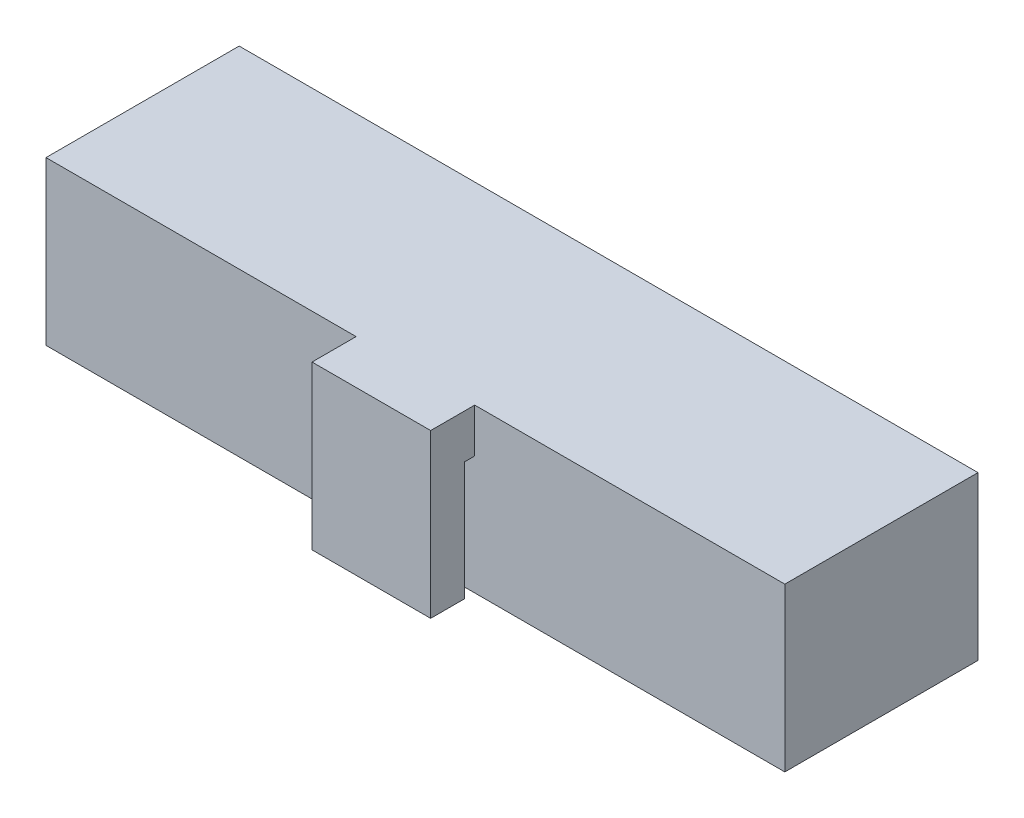
SolidWorks part; units mm, degrees
ref_plane "Plan de face" through (0, 0, 0) normal (0, 0, 1) x (1, 0, 0)
ref_plane "Plan de dessus" through (0, 0, 0) normal (0, 1, 0) x (1, 0, 0)
ref_plane "Plan de droite" through (0, 0, 0) normal (1, 0, 0) x (0, 0, -1)
sketch "Esquisse1" plane through (0, 0, 0) normal (0, 0, 1) x (1, 0, 0)
  line L1 (-10.9, -2.4) -> (10.9, -2.4)
  line L2 (-10.9, -2.4) -> (-10.9, 2.4)
  line L3 (-10.9, 2.4) -> (10.9, 2.4)
  line L4 (10.9, -2.4) -> (10.9, 2.4)
  line L5 (-10.9, -2.4) -> (10.9, 2.4) construction
  line L6 (-10.9, 2.4) -> (10.9, -2.4) construction
  point P0 (0, 0)
  dimension "D1" = 21.8
  dimension "D2" = 4.8
extrude "Boss.-Extru.1" add sketch "Esquisse1" along normal blind 7
sketch "Esquisse2" plane through (0, 0, 7) normal (0, 0, 1) x (1, 0, 0)
  line L0 (-1.75, -6.7758) -> (-1.75, 6.0976)
  line L1 (1.75, -7.2459) -> (1.75, 4.6423)
  line L2 (10.9, 2.4) -> (-10.9, 2.4) construction
  line L3 (-10.9, -2.4) -> (-1.75, -2.4)
  line L4 (-10.9, -2.4) -> (-10.9, 2.4)
  line L5 (-10.9, 2.4) -> (-1.75, 2.4)
  line L6 (-1.75, -2.4) -> (-1.75, 2.4)
  line L8 (10.9, -2.4) -> (1.75, -2.4)
  line L9 (10.9, -2.4) -> (10.9, 2.4)
  line L10 (10.9, 2.4) -> (1.75, 2.4)
  line L11 (1.75, -2.4) -> (1.75, 2.4)
  dimension "D1" = 1.75
  dimension "D2" = 1.75
extrude "Enlèv. mat.-Extru.1" cut sketch "Esquisse2" against normal blind 1.3 contours L4 L3 L6 L5 | L9 L8 L11 L10
sketch "Esquisse3" plane through (0, -2.4, 0) normal (0, -1, 0) x (1, 0, 0)
  line L0 (-2.9889, 6) -> (5.1605, 6)
  line L1 (10.9, 5.7) -> (1.75, 5.7) construction
  line L2 (-1.75, 5.7) -> (-1.75, 7) construction
  line L3 (1.75, 5.7) -> (-1.75, 5.7)
  line L4 (1.75, 5.7) -> (1.75, 6)
  line L5 (1.75, 6) -> (-1.75, 6)
  line L6 (-1.75, 5.7) -> (-1.75, 6)
  dimension "D1" = 0.3
extrude "Enlèv. mat.-Extru.2" cut sketch "Esquisse3" against normal blind 3.5 contours L4 L3 L6 L5
